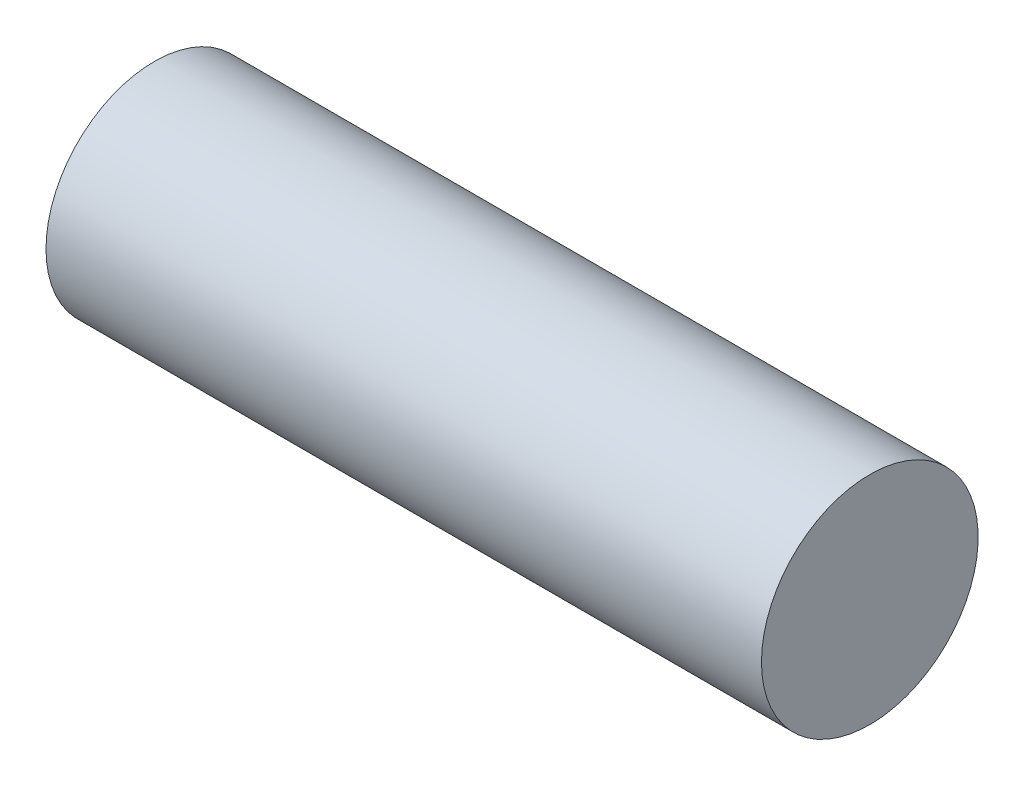
SolidWorks part; units mm, degrees
ref_plane "Front Plane" through (0, 0, 0) normal (0, 0, 1) x (1, 0, 0)
ref_plane "Top Plane" through (0, 0, 0) normal (0, 1, 0) x (1, 0, 0)
ref_plane "Right Plane" through (0, 0, 0) normal (1, 0, 0) x (0, 0, -1)
sketch "Sketch2" plane through (0, 0, 0) normal (0, 0, 1) x (1, 0, 0)
  line L5 (-35, 10.6) -> (35, 10.6)
  line L6 (-35, 10.6) -> (-35, 0)
  line L7 (-35, 0) -> (35, 0)
  line L8 (35, 10.6) -> (35, 0)
  point P4 (0, 0)
  dimension "D1" = 10.6
  dimension "D2" = 70
revolve "Revolve1" add sketch "Sketch2" angle 360 about L7
